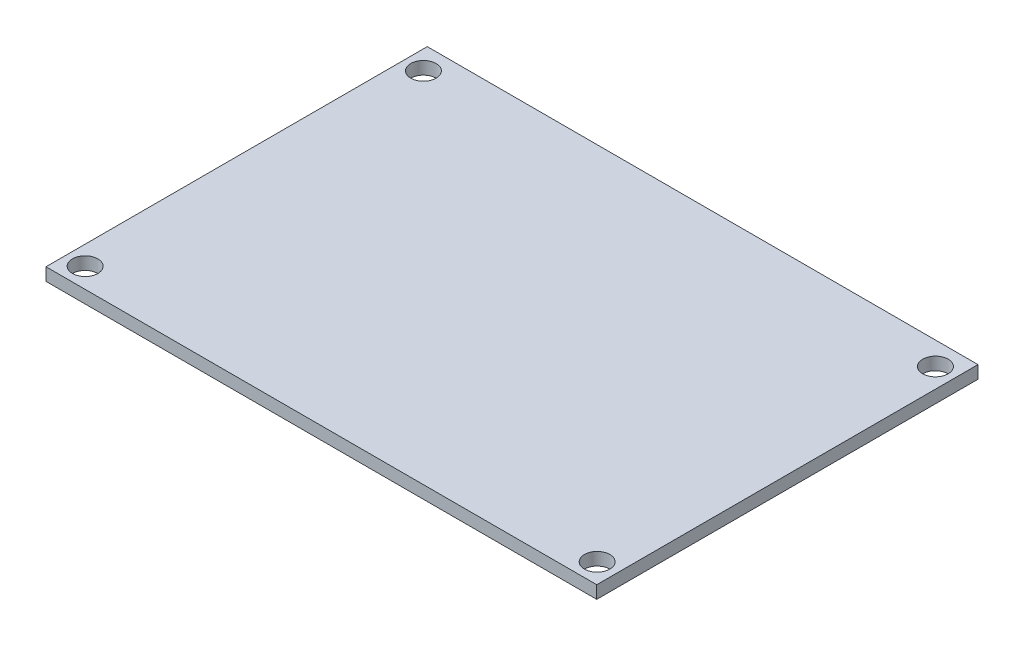
SolidWorks part; units mm, degrees
ref_plane "Front Plane" through (0, 0, 0) normal (0, 0, 1) x (1, 0, 0)
ref_plane "Top Plane" through (0, 0, 0) normal (0, 1, 0) x (1, 0, 0)
ref_plane "Right Plane" through (0, 0, 0) normal (1, 0, 0) x (0, 0, -1)
sketch "Sketch1" plane through (0, 0, 0) normal (0, 1, 0) x (1, 0, 0)
  line L1 (-32.5, 22.5) -> (32.5, 22.5)
  line L2 (-32.5, 22.5) -> (-32.5, -22.5)
  line L3 (-32.5, -22.5) -> (32.5, -22.5)
  line L4 (32.5, 22.5) -> (32.5, -22.5)
  line L5 (-32.5, 22.5) -> (32.5, -22.5) construction
  line L6 (-32.5, -22.5) -> (32.5, 22.5) construction
  point P0 (0, 0)
extrude "Boss-Extrude1" add sketch "Sketch1" along normal blind 1.5
sketch "Sketch2" plane through (0, 1.5, 0) normal (0, 1, 0) x (1, 0, 0)
  circle A0 centre (-30.2498, 19.7943) radius 1.5
  circle A1 centre (30.1821, 19.7943) radius 1.5
  circle A2 centre (30.1821, -20.1327) radius 1.5
  circle A3 centre (-30.2498, -20.1327) radius 1.5
extrude "Cut-Extrude1" cut sketch "Sketch2" against normal through all
